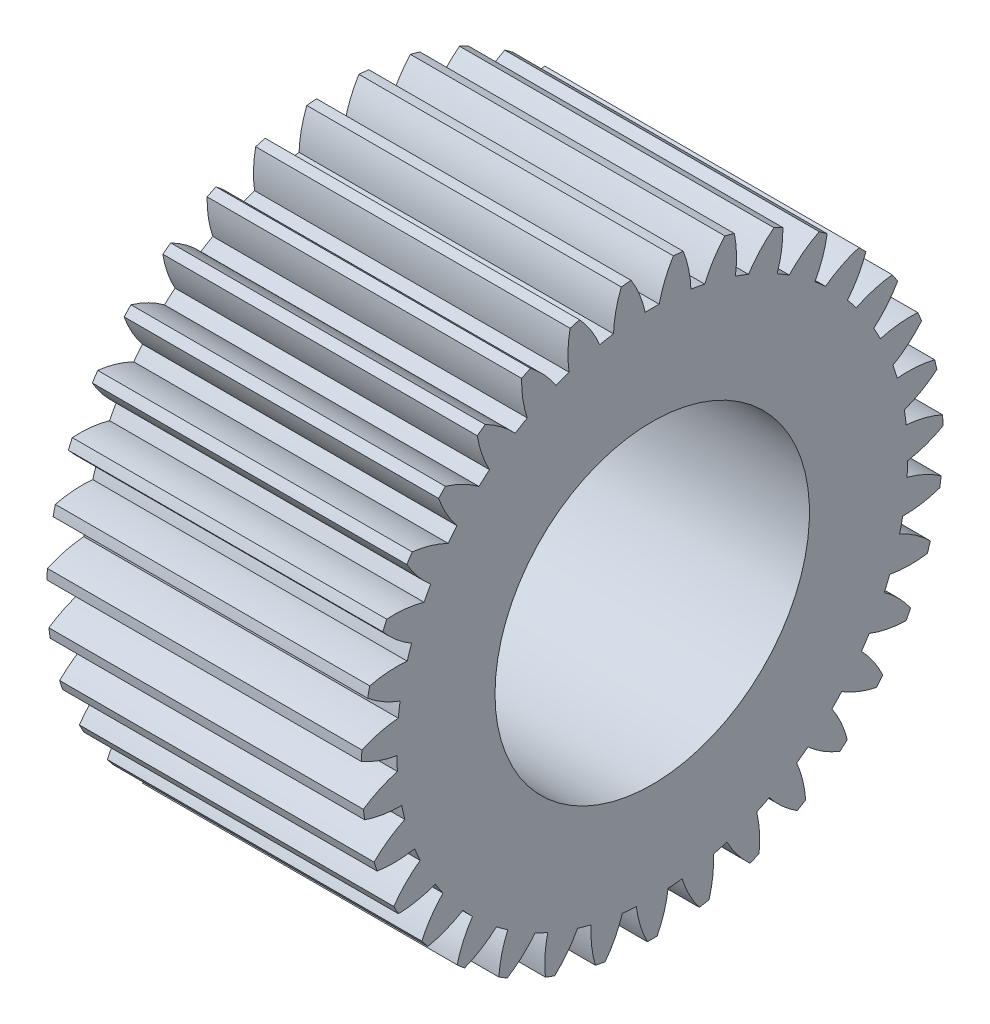
SolidWorks part; units mm, degrees
ref_plane "Plane1" through (0, 0, 0) normal (0, 0, 1) x (1, 0, 0)
ref_plane "Plane2" through (0, 0, 0) normal (0, 1, 0) x (1, 0, 0)
ref_plane "Plane3" through (0, 0, 0) normal (1, 0, 0) x (0, 0, -1)
sketch "HoldingSke" plane through (0, 0, 0) normal (0, 1, 0) x (1, 0, 0)
  line L0 (0, 0) -> (3.2766, -2.2943)
  line L1 (-15, 0) -> (100, 0) construction
  line L2 (0, 0) -> (-2.1039, 2.3779)
  line L3 (0, 0) -> (-11.863, 4.5341)
  line L4 (0, 0) -> (7.0742, 4.9534)
  line L5 (0, 0) -> (-46.8476, -17.4728)
  line L6 (0, 0) -> (-4.1448, -2.7965)
  line L7 (-2.1039, 2.3779) -> (8.6586, 51.2059)
  line L8 (-76.2, 54.61) -> (-75.3, 54.61)
  line L9 (-71.009, 38.7566) -> (-53.1078, 45.2721)
  line L10 (-76.2, 71.12) -> (104.1128, 71.12)
  line L11 (0, 0) -> (-5, 0)
  line L12 (-76.2, 101.6) -> (-76.192, 101.6)
  line L13 (24.9733, 27.94) -> (52.9518, 28.4284)
  line L14 (24.9733, 27.94) -> (24.9743, 27.94)
  line L15 (24.9733, 27.94) -> (100.4006, 29.5858)
  line L16 (-63.627, -0.25) -> (-12.827, -0.25)
  circle A0 centre (0, 0) radius 2.5
  circle A1 centre (0, 0) radius 4.0615
  circle A2 centre (0, 0) radius 37.5
  circle A3 centre (0, 0) radius 2.5
  dimension "MHD" = 8.123
  dimension "Hub_dia" = 75
  dimension "Bore" = 5
  dimension "MBD" = 5
  dimension "Num_teeth" = 35
  dimension "Pitch" = 4
  dimension "Overall_len" = 50
  dimension "Show_teeth" = 35
  dimension "Thickness" = 5
  dimension "OAL" = 50.0001
  dimension "T_dim" = 0.9
  dimension "Ap" = 20
  dimension "H" = 19.05
  dimension "Pitch_radius" = 180.3128
  dimension "Width" = 5
  dimension "Backlash" = 0.008
  dimension "Addendum_fac" = 1
  dimension "Dedendum_fac" = 1.25
  dimension "Clearance_fac" = 0.25
  dimension "Dedendum_add" = 0.001
  dimension "Module" = 0.25
sketch "BasProSke" plane through (0, 0, 0) normal (0, 1, 0) x (1, 0, 0)
  line L0 (-10, 0) -> (60, 0) construction
  line L1 (0, 0) -> (0, 4.625)
  line L2 (0, 0) -> (5, 0)
  line L3 (5, 0) -> (5, 4.625)
  line L4 (5, 4.625) -> (0, 4.625)
  dimension "Thickness" = 5
  dimension "Diameter" = 9.25
revolve "Base-Revolve" add sketch "BasProSke" angle 360 about L0
sketch "TooCutSke" plane through (0, 0, 0) normal (1, 0, 0) x (0, 0, -1)
  line L1 (0, 0) -> (0, 107) construction
  line L2 (0, 0) -> (-0.2103, 4.3699) construction
  line L3 (0, 0) -> (-0.7837, 8.7072) construction
  line L4 (-0.2103, 4.3699) -> (-0.3918, 4.3536) construction
  arc A0 (0.1115, 4.06) -> (-0.1115, 4.06) centre (0, 0) ccw
  arc A1 (0.3521, 4.6371) -> (-0.3521, 4.6371) centre (0, 0) ccw
  circle A2 centre (0, 0) radius 4.375 construction
  circle A3 centre (0, 0) radius 4.1112 construction
  arc A4 (-0.1115, 4.06) -> (-0.3521, 4.6371) centre (-1.821, 3.6858) ccw
  arc A5 (0.3521, 4.6371) -> (0.1115, 4.06) centre (1.821, 3.6858) ccw
  dimension "Root_dia" = 8.123
  dimension "Overcut_dia" = 9.3008
  dimension "Pitch_dia" = 8.75
  dimension "Base_dia" = 8.2223
  dimension "Flank_rad" = 1.75
  dimension "Half_ang" = 5.143
  dimension "Half_CT" = 0.1823
extrude "ToothCut" cut sketch "TooCutSke" along normal through all
fillet "Breaks" [suppressed] radius 0.005
fillet "RootFillets" [suppressed] radius 0.0635
pattern_circular "TeethCuts" count 35 every 10.286 about axis through (-10, 0, 0) along (1, 0, 0) of "ToothCut", "RootFillets", "Breaks"
sketch "HubNeaOneSke" plane through (0, 0, 0) normal (-1, 0, 0) x (0, 0, 1)
  circle A0 centre (0, 0) radius 4.0615
  dimension "Diameter" = 8.123
extrude "HubNearOne" [suppressed] add sketch "HubNeaOneSke" along normal blind 45.0001
sketch "HubNeaBotSke" plane through (0, 0, 0) normal (-1, 0, 0) x (0, 0, 1)
  circle A0 centre (0, 0) radius 4.0615
  dimension "Diameter" = 8.123
extrude "HubNearBoth" [suppressed] add sketch "HubNeaBotSke" along normal blind 22.5
ref_plane "FarPln" through (5, 0, 0) normal (1, 0, 0) x (0, 0, -1)
sketch "HubFarSke" plane through (5, 0, 0) normal (1, 0, 0) x (0, 0, -1)
  circle A0 centre (0, 0) radius 4.0615
  dimension "Diameter" = 8.123
extrude "HubFar" [suppressed] add sketch "HubFarSke" along normal blind 22.5
sketch "BorSke" plane through (0, 0, 0) normal (1, 0, 0) x (0, 0, -1)
  circle A0 centre (0, 0) radius 2.5
  dimension "Diameter" = 5
extrude "Bore" cut sketch "BorSke" along normal mid plane 100.0001
sketch "KeySke" plane through (0, 0, 0) normal (1, 0, 0) x (0, 0, -1)
  line L0 (-1, 0) -> (-1, 3.4)
  line L1 (-1, 3.4) -> (1, 3.4)
  line L2 (1, 3.4) -> (1, 0)
  line L3 (0, 0) -> (0, 34) construction
  line L4 (-1, 0) -> (1, 0)
  dimension "Offset" = 3.4
  dimension "Width" = 2
extrude "Keyway" [suppressed] cut sketch "KeySke" along normal mid plane 100.0001
pattern_circular "Keyway2" [suppressed] count 2 every 90 about axis through (-10, 0, 0) along (1, 0, 0)
equation "' \"Module@HoldingSke\" = 6.35"
equation "' \"Num_teeth@HoldingSke\" = 12"
equation "' \"Ap@HoldingSke\" =  20"
equation "' \"Ap@HoldingSke\" = 20"
equation "' \"Width@HoldingSke\" = 0.5 * 25.4"
equation "' \"Hub_dia@HoldingSke\"= 1 * 25.4"
equation "' \"Hub_dia@HoldingSke\" = 1 * 25.4"
equation "' \"Overall_len@HoldingSke\" = 1.0 * 25.4"
equation "' \"Bore@HoldingSke\" = 0.75 * 25.4"
equation "' \"T_dim@HoldingSke\" = 0.1 * 25.4"
equation "' \"Width@KeySke\" = 0.25 * 25.4"
equation "' \"Show_teeth@HoldingSke\" = 13"
equation "' \"Backlash@HoldingSke\" = 0.009 * 25.4"
equation "' \"Addendum_fac@HoldingSke\" = 1.0"
equation "' \"Dedendum_fac@HoldingSke\" = 1.25"
equation "' \"Dedendum_add@HoldingSke\" = 0.00005 * 25.4"
equation "' \"Clearance_fac@HoldingSke\" = 0.25"
equation "\"Pitch@HoldingSke\" = 1 / \"Module@HoldingSke\""
equation "\"Overcut_dia@TooCutSke\" = (\"Num_teeth@HoldingSke\" + 2 * \"Addendum_fac@HoldingSke\") / \"Pitch@HoldingSke\" + 0.002 * 25.4"
equation "\"Pitch_dia@TooCutSke\" = \"Num_teeth@HoldingSke\" / \"Pitch@HoldingSke\""
equation "\"Base_dia@TooCutSke\" = \"Num_teeth@HoldingSke\" / \"Pitch@HoldingSke\" * cos((\"Ap@HoldingSke\"  * 3.14159265 / 180))"
equation "\"Root_dia@TooCutSke\" = (\"Num_teeth@HoldingSke\" + 2) / \"Pitch@HoldingSke\" - 2 * (\"Addendum_fac@HoldingSke\" + \"Dedendum_fac@HoldingSke\") / \"Pitch@HoldingSke\" - \"Dedendum_add@HoldingSke\" * 2"
equation "\"Half_ang@TooCutSke\" = 180 / \"Num_teeth@HoldingSke\""
equation "\"Half_CT@TooCutSke\" = \"Num_teeth@HoldingSke\" / \"Pitch@HoldingSke\" * sin((3.14159265 / 2 / \"Num_teeth@HoldingSke\")) / 2 - 7 * \"Backlash@HoldingSke\" / 4"
equation "\"Flank_rad@TooCutSke\" = \"Num_teeth@HoldingSke\" / \"Pitch@HoldingSke\" / 5"
equation "\"Radius@RootFillets\" = \"Clearance_fac@HoldingSke\" / \"Pitch@HoldingSke\" + \"Dedendum_add@HoldingSke\""
equation "\"Break_rad@Breaks\" = 0.02 / \"Pitch@HoldingSke\""
equation "\"Thickness@HoldingSke\" = \"Width@HoldingSke\""
equation "\"OAL@HoldingSke\" = \"Thickness@HoldingSke\""
equation "\"MHD@HoldingSke\" = (\"Num_teeth@HoldingSke\" + 2) / \"Pitch@HoldingSke\" - 2 * (\"Addendum_fac@HoldingSke\" + \"Dedendum_fac@HoldingSke\")  / \"Pitch@HoldingSke\" - \"Dedendum_add@HoldingSke\" * 2"
equation "\"MBD@HoldingSke\" = (\"Num_teeth@HoldingSke\" + 2) / \"Pitch@HoldingSke\" - 2 * (\"Addendum_fac@HoldingSke\" + \"Dedendum_fac@HoldingSke\")  / \"Pitch@HoldingSke\" - \"Dedendum_add@HoldingSke\" * 2 - 0.002 * 25.4"
equation "\"MHD@HoldingSke\" = ((sgn( \"MHD@HoldingSke\" - \"Hub_dia@HoldingSke\" )-1)*( \"MHD@HoldingSke\" - \"Hub_dia@HoldingSke\" ))/-2+ \"Hub_dia@HoldingSke\""
equation "\"MBD@HoldingSke\" = ((sgn( \"MBD@HoldingSke\" - \"Bore@HoldingSke\" )-1)*( \"MBD@HoldingSke\" - \"Bore@HoldingSke\" ))/-2+ \"Bore@HoldingSke\""
equation "\"OAL@HoldingSke\" = ((sgn( \"OAL@HoldingSke\" - \"Overall_len@HoldingSke\" )+1)*( \"OAL@HoldingSke\" - \"Overall_len@HoldingSke\" ))/2 + \"Overall_len@HoldingSke\" + 0.000002 * 25.4"
equation "\"Num_teeth@TeethCuts\" = int( \"Show_teeth@HoldingSke\" ) + 1"
equation "\"Num_teeth@TeethCuts\" = ((sgn( \"Num_teeth@TeethCuts\" - \"Num_teeth@HoldingSke\" )-1)*( \"Num_teeth@TeethCuts\" - \"Num_teeth@HoldingSke\" ))/-2+ \"Num_teeth@HoldingSke\""
equation "\"Num_teeth@TeethCuts\" = ((sgn( \"Num_teeth@TeethCuts\" - 2.0)+1)*( \"Num_teeth@TeethCuts\" - 2.0))/2 +2.0"
equation "\"Angle@TeethCuts\" = 360.0 / \"Num_teeth@HoldingSke\""
equation "\"Diameter@BasProSke\" = (\"Num_teeth@HoldingSke\" + 2 * \"Addendum_fac@HoldingSke\") / \"Pitch@HoldingSke\""
equation "\"Thickness@BasProSke\"  = \"Thickness@HoldingSke\""
equation "' \"Fillet_rad@BasProSke\" =  \"Thickness@HoldingSke\" * 0.05"
equation "' \"Fillet_rad@BasProSke\" = \"Thickness@HoldingSke\" * 0.05"
equation "\"MHD@HoldingSke\" = ((sgn( \"MHD@HoldingSke\" - \"Root_dia@TooCutSke\" )-1)*( \"MHD@HoldingSke\" - \"Root_dia@TooCutSke\" ))/-2+ \"Root_dia@TooCutSke\""
equation "\"Diameter@HubNeaOneSke\" = \"MHD@HoldingSke\""
equation "\"Length@HubNearOne\" = \"OAL@HoldingSke\" - \"Thickness@BasProSke\""
equation "\"Diameter@HubNeaBotSke\" = \"MHD@HoldingSke\""
equation "\"Length@HubNearBoth\" = ( \"OAL@HoldingSke\" - \"Thickness@BasProSke\" ) / 2.0"
equation "\"Thickness@FarPln\" = \"Thickness@BasProSke\""
equation "\"Diameter@HubFarSke\" = \"MHD@HoldingSke\""
equation "\"Length@HubFar\" = ( \"OAL@HoldingSke\" - \"Thickness@BasProSke\" ) / 2.0"
equation "\"Diameter@BorSke\" = \"MBD@HoldingSke\""
equation "\"D1@Bore\" = \"OAL@HoldingSke\" * 2.0"
equation "\"D1@Keyway\" = \"OAL@HoldingSke\" * 2.0"
equation "\"Offset@KeySke\" = \"T_dim@HoldingSke\" + \"MBD@HoldingSke\" / 2.0"
